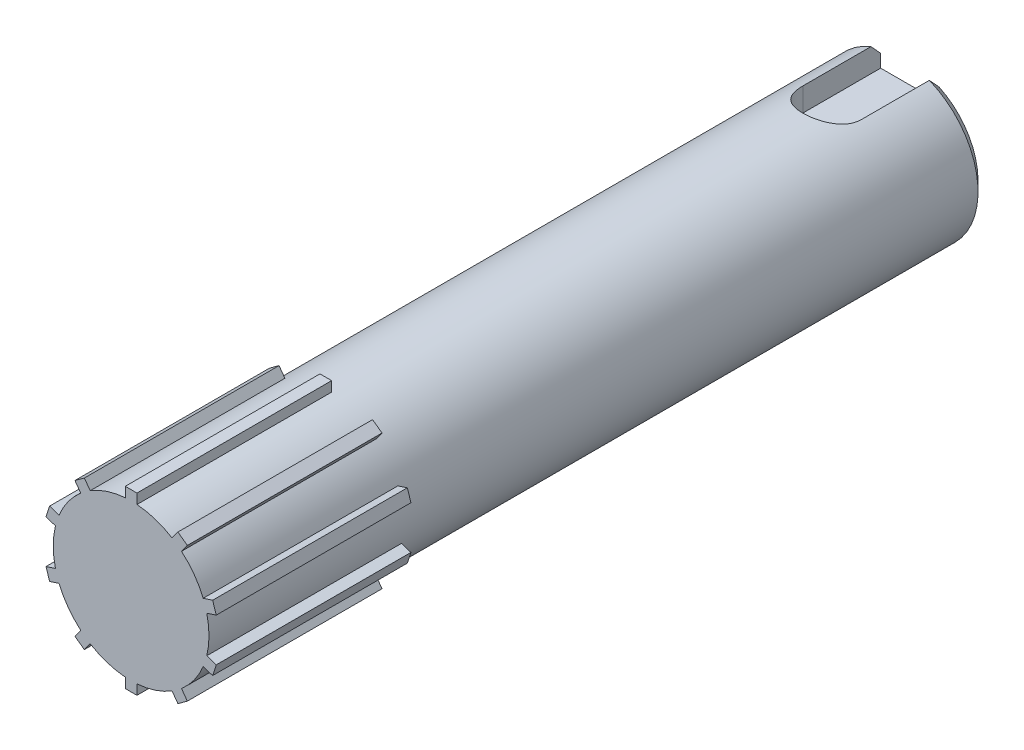
SolidWorks part; units mm, degrees
ref_plane "Front Plane" through (0, 0, 0) normal (0, 0, 1) x (1, 0, 0)
ref_plane "Top Plane" through (0, 0, 0) normal (0, 1, 0) x (1, 0, 0)
ref_plane "Right Plane" through (0, 0, 0) normal (1, 0, 0) x (0, 0, -1)
sketch "Sketch1" plane through (0, 0, 0) normal (0, 0, 1) x (1, 0, 0)
  circle A0 centre (0, 0) radius 4
  dimension "D1" = 8
extrude "Boss-Extrude1" add sketch "Sketch1" along normal blind 40
sketch "Sketch2" plane through (0, 0, 0) normal (0, 1, 0) x (1, 0, 0)
  line L0 (0, 0) -> (0, -4) construction
  line L1 (1.5, 0) -> (1.5, -4)
  line L2 (-1.5, 0) -> (-1.5, -4)
  arc A0 (1.5, 0) -> (-1.5, 0) centre (0, 0) ccw
  arc A1 (-1.5, -4) -> (1.5, -4) centre (0, -4) ccw
  point P3 (0, -2)
  dimension "D1" = 1.5
  dimension "D2" = 4
extrude "Cut-Extrude1" cut sketch "Sketch2" along normal through all from offset 2.5
chamfer "Chamfer1" distance 0.5 angle 45 1 edges at (0, -4, 0)
sketch "Sketch3" plane through (0, 0, 40) normal (0, 0, 1) x (1, 0, 0)
  line L0 (0, 4) -> (0, 0) construction
  line L2 (-0.3, 4.5) -> (0.3, 4.5)
  line L3 (-0.3, 4.5) -> (-0.3, 3.5)
  line L4 (-0.3, 3.5) -> (0.3, 3.5)
  line L5 (0.3, 4.5) -> (0.3, 3.5)
  line L6 (0, 3.5) -> (0, 4.5) construction
  line L7 (-0.3, 4) -> (0.3, 4) construction
  circle A0 centre (0, 0) radius 4 construction
  dimension "D1" = 0.6
  dimension "D2" = 4.5
extrude "Boss-Extrude2" add sketch "Sketch3" against normal blind 10
pattern_circular "CirPattern1" count 10 over 360 about axis through (0, 0, 0) along (0, 0, 1) of "Boss-Extrude2"
